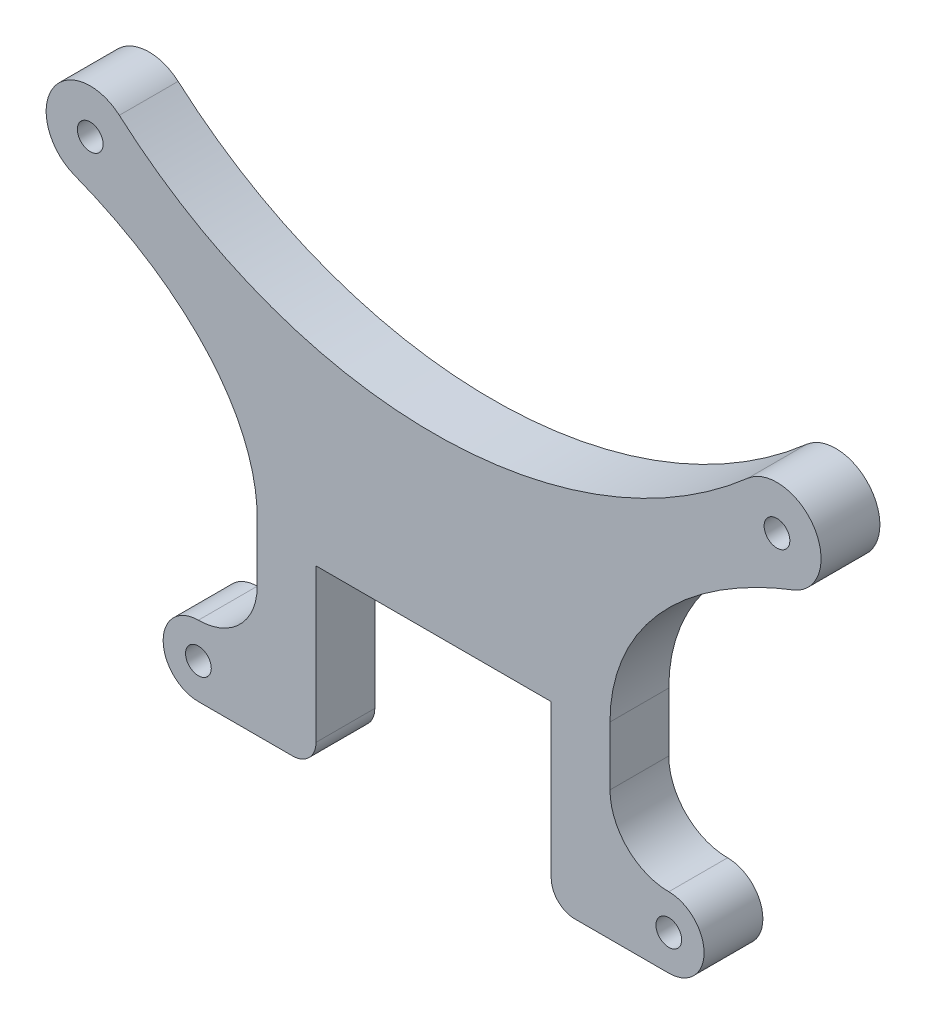
SolidWorks part; units mm, degrees
ref_plane "Front Plane" through (0, 0, 0) normal (0, 0, 1) x (1, 0, 0)
ref_plane "Top Plane" through (0, 0, 0) normal (0, 1, 0) x (1, 0, 0)
ref_plane "Right Plane" through (0, 0, 0) normal (1, 0, 0) x (0, 0, -1)
sketch "Sketch1" plane through (0, 0, 0) normal (0, 0, 1) x (1, 0, 0)
  line L0 (0, 32.7025) -> (0, -57.25) construction
  line L1 (12.7, 0) -> (-12.7, 0)
  line L2 (-12.7, 0) -> (-12.7, -16.51)
  line L3 (-15.24, -19.05) -> (-25.4, -19.05)
  line L4 (-37.084, 32.7025) -> (18.6004, 32.7025) construction
  line L5 (-19.05, -5.08) -> (-19.05, 1.27)
  line L6 (12.7, 0) -> (12.7, -16.51)
  line L7 (15.24, -19.05) -> (25.4, -19.05)
  line L8 (19.05, -5.08) -> (19.05, 1.27)
  arc A0 (-25.4, -19.05) -> (-25.4, -11.43) centre (-25.4, -15.24) cw
  arc A1 (-33.9417, 31.5188) -> (-38.8078, 23.5004) centre (-37.084, 27.94) ccw
  arc A2 (33.9417, 31.5188) -> (-33.9417, 31.5188) centre (0, 70.1756) cw
  arc A3 (-25.4, -11.43) -> (-19.05, -5.08) centre (-25.4, -5.08) ccw
  circle A4 centre (-37.084, 27.94) radius 1.3891
  circle A5 centre (-25.4, -15.24) radius 1.3891
  circle A6 centre (25.4, -15.24) radius 1.3891
  arc A7 (25.4, -19.05) -> (25.4, -11.43) centre (25.4, -15.24) ccw
  arc A8 (25.4, -11.43) -> (19.05, -5.08) centre (25.4, -5.08) cw
  circle A9 centre (37.084, 27.94) radius 1.3891
  arc A10 (33.9417, 31.5188) -> (38.8078, 23.5004) centre (37.084, 27.94) cw
  arc A11 (-15.24, -19.05) -> (-12.7, -16.51) centre (-15.24, -16.51) ccw
  arc A12 (15.24, -19.05) -> (12.7, -16.51) centre (15.24, -16.51) cw
  ellipse E0 centre (-60.8178, 1.27) end of major axis (-19.05, 1.27) minor radius 26.1568 (-38.8078, 23.5004) -> (-19.05, 1.27) cw
  ellipse E1 centre (60.8178, 1.27) end of major axis (102.5857, 1.27) minor radius 26.1568 (38.8078, 23.5004) -> (19.05, 1.27) ccw
  point P9 (-37.084, 27.94)
  point P14 (0, 18.7325)
  point P28 (0, 0)
  point P47 (-12.7, -19.05)
  point P50 (12.7, -19.05)
  dimension "D4" = 3.81
  dimension "D7" = 9.525
  dimension "D9" = 6.35
  dimension "D12" = 2.7781
  dimension "D13" = 2.7781
  dimension "D14" = 2.54
  dimension "D15" = 2.54
  dimension "D1" = 12.7
  dimension "D2" = 19.05
  dimension "D3" = 25.4
  dimension "D5" = 11.684
  dimension "D6" = 43.18
  dimension "D8" = 13.97
  dimension "D10" = 6.35
  dimension "D11" = 60.8178
extrude "Boss-Extrude1" add sketch "Sketch1" along normal blind 6.35
